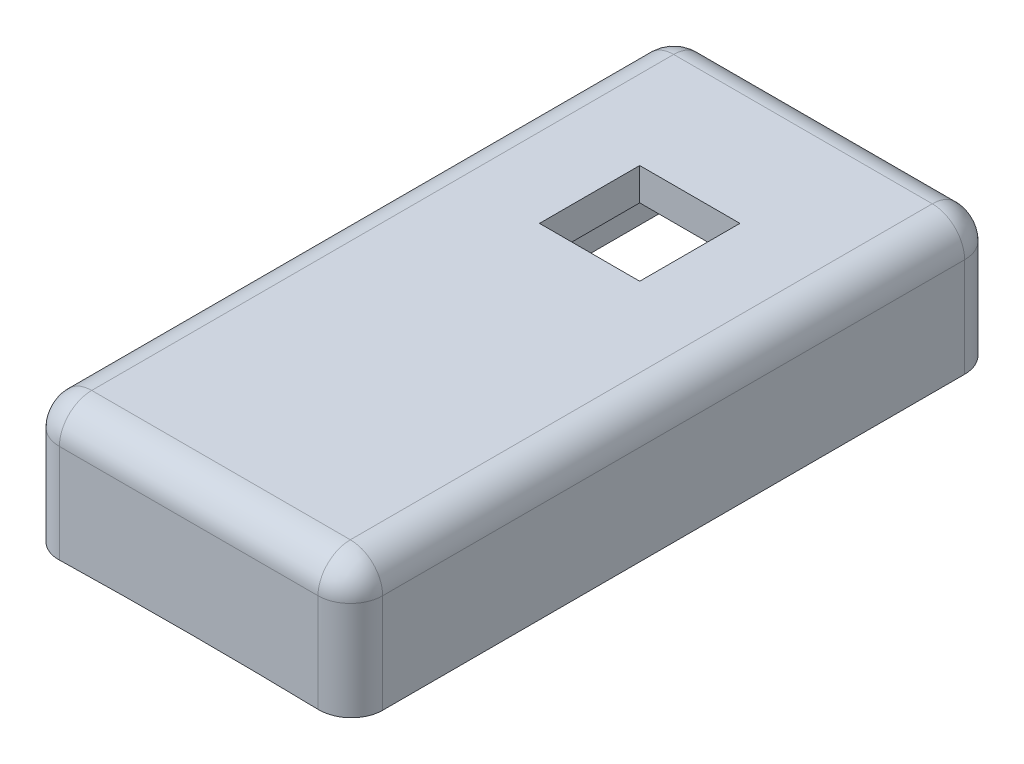
SolidWorks part; units mm, degrees
ref_plane "Front Plane" through (0, 0, 0) normal (0, 0, 1) x (1, 0, 0)
ref_plane "Top Plane" through (0, 0, 0) normal (0, 1, 0) x (1, 0, 0)
ref_plane "Right Plane" through (0, 0, 0) normal (1, 0, 0) x (0, 0, -1)
sketch "Sketch3" plane through (0, 0, 0) normal (0, 0, 1) x (1, 0, 0)
  line L0 (0, 0) -> (0, 915) construction
  line L1 (0, 915) -> (0, 935) construction
  line L2 (-25, 935) -> (25, 935)
  line L3 (-25, 935) -> (-25, 914.6584)
  line L4 (25, 935) -> (25, 914.6584)
  circle A0 centre (0, 0) radius 915
  dimension "D1" = 1830
  dimension "D2" = 20
  dimension "D3" = 50
extrude "Boss-Extrude1" add sketch "Sketch3" along normal blind 100 contours A0 L4 L2 L3
sketch "Sketch4" plane through (0, 935, 0) normal (0, 1, 0) x (1, 0, 0)
  line L0 (0, -100) -> (0, -95) construction
  line L1 (-20, -5) -> (20, -5)
  line L2 (-20, -5) -> (-20, -95)
  line L3 (-20, -95) -> (20, -95)
  line L4 (20, -5) -> (20, -95)
  line L5 (-25, -100) -> (25, -100) construction
  line L6 (25, -50) -> (20, -50) construction
  line L7 (25, -100) -> (25, 0) construction
  line L8 (-25, -50) -> (-20, -50) construction
  line L9 (-25, -100) -> (-25, 0) construction
  line L10 (0, 0) -> (0, -5) construction
  line L11 (-25, 0) -> (25, 0) construction
  dimension "D1" = 5
extrude "Cut-Extrude1" cut sketch "Sketch4" against normal blind 150
ref_plane "Plane1" through (-25, 935, 0) normal (0, 0, -1) x (-1, 0, 0)
sketch "Sketch6" plane through (0, 935, 0) normal (0, 1, 0) x (1, 0, 0)
  line L0 (0, -22.5) -> (0, -5) construction
  line L1 (25, 0) -> (-25, 0)
  line L2 (25, 0) -> (25, -100)
  line L3 (25, -100) -> (-25, -100)
  line L4 (-25, 0) -> (-25, -100)
  line L5 (-7.75, -22.5) -> (7.75, -22.5)
  line L6 (-7.75, -22.5) -> (-7.75, -38)
  line L7 (-7.75, -38) -> (7.75, -38)
  line L8 (7.75, -22.5) -> (7.75, -38)
  line L9 (20, -5) -> (-20, -5) construction
  dimension "D1" = 15.5
  dimension "D2" = 15.5
  dimension "D3" = 17.5
extrude "Boss-Extrude2" add sketch "Sketch6" against normal blind 5
fillet "Fillet1" radius 5 8 edges at (0, 935, 100) (-25, 935, 50) (0, 935, 0) (25, 935, 50) (25, 924.8292, 0) (-25, 924.8292, 0) (-25, 924.8292, 100) (25, 924.8292, 100)
sketch "Sketch7" plane through (-25, 0, 0) normal (-1, 0, 0) x (0, 0, 1)
  line L1 (95, 914.6584) -> (80, 914.6584)
  line L2 (95, 914.6584) -> (95, 919.6584)
  line L3 (95, 919.6584) -> (80, 919.6584)
  line L4 (80, 914.6584) -> (80, 919.6584)
  dimension "D1" = 15
  dimension "D2" = 5
extrude "Cut-Extrude2" cut sketch "Sketch7" against normal blind 5
